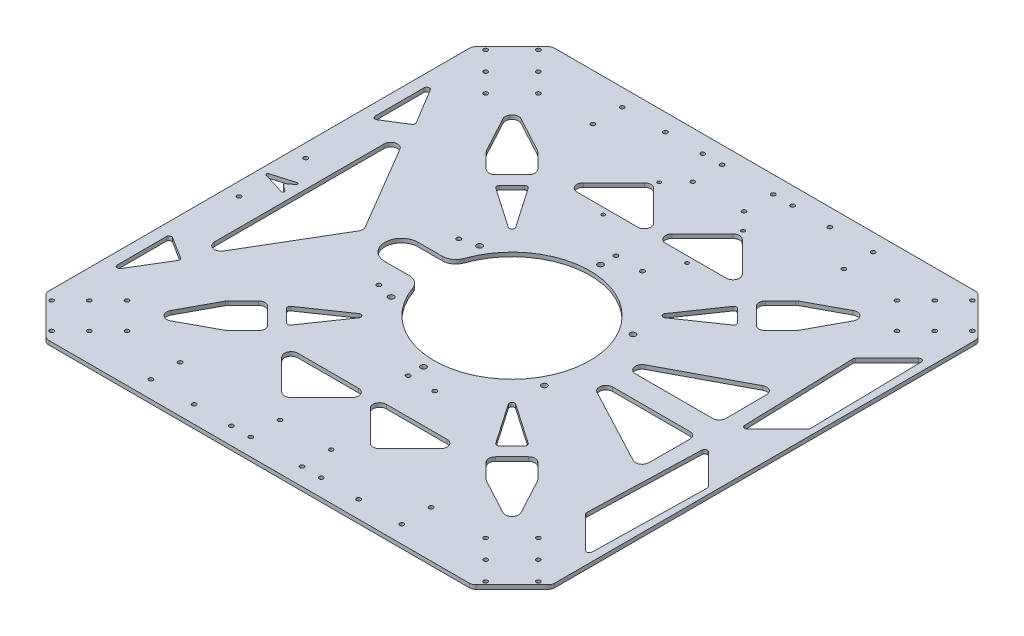
SolidWorks part; units mm, degrees
material "Hexcel AS4C (3000 丝)"
ref_plane "前视基准面" through (0, 0, 0) normal (0, 0, 1) x (1, 0, 0)
ref_plane "上视基准面" through (0, 0, 0) normal (0, 1, 0) x (1, 0, 0)
ref_plane "右视基准面" through (0, 0, 0) normal (1, 0, 0) x (0, 0, -1)
sketch "草图1" plane through (0, 0, 0) normal (0, 1, 0) x (1, 0, 0)
  line L0 (-190, 160) -> (-160, 190)
  line L1 (-160, 190) -> (160, 190)
  line L2 (-190, 160) -> (-190, -160)
  line L3 (-160, -190) -> (160, -190)
  line L4 (190, 160) -> (190, -160)
  line L5 (-190, 190) -> (190, -190) construction
  line L6 (-190, -190) -> (190, 190) construction
  line L7 (-190, -160) -> (-160, -190)
  line L8 (160, -190) -> (190, -160)
  line L9 (160, 190) -> (190, 160)
  circle A0 centre (0, 0) radius 58.5
  point P0 (0, 0)
  dimension "D3" = 117
  dimension "D1" = 380
  dimension "D2" = 380
extrude "凸台-拉伸1" add sketch "草图1" along normal blind 3
sketch "草图2" plane through (0, 3, 0) normal (0, 1, 0) x (1, 0, 0)
  line L1 (33.5, -23.5) -> (-33.5, -23.5) construction
  line L2 (33.5, -23.5) -> (33.5, 23.5) construction
  line L3 (33.5, 23.5) -> (-33.5, 23.5) construction
  line L4 (-33.5, -23.5) -> (-33.5, 23.5) construction
  line L5 (33.5, -23.5) -> (-33.5, 23.5) construction
  line L6 (33.5, 23.5) -> (-33.5, -23.5) construction
  circle A0 centre (-33.5, 23.5) radius 1.6
  circle A1 centre (33.5, 23.5) radius 1.6
  circle A2 centre (33.5, -23.5) radius 1.6
  circle A3 centre (-33.5, -23.5) radius 1.6
  point P0 (0, 0)
  dimension "D3" = 3.2
  dimension "D1" = 67
  dimension "D2" = 47
extrude "切除-拉伸1" [suppressed] cut sketch "草图2" against normal through all
sketch "草图3" plane through (0, 3, 0) normal (0, 1, 0) x (1, 0, 0)
  line L0 (0, 0) -> (-175, -175) construction
  line L1 (-190, -160) -> (-160, -190) construction
  line L2 (-162.9792, -182.7782) -> (-134.6949, -154.4939) construction
  circle A1 centre (-162.9792, -182.7782) radius 1.55
  circle A2 centre (-182.7782, -162.9792) radius 1.55
  circle A3 centre (-148.837, -168.636) radius 1.55
  circle A4 centre (-134.6949, -154.4939) radius 1.55
  circle A5 centre (-168.636, -148.837) radius 1.55
  circle A6 centre (-154.4939, -134.6949) radius 1.55
  circle A7 centre (-162.9792, 182.7782) radius 1.55
  circle A8 centre (-148.837, 168.636) radius 1.55
  circle A9 centre (-134.6949, 154.4939) radius 1.55
  circle A10 centre (-154.4939, 134.6949) radius 1.55
  circle A11 centre (-168.636, 148.837) radius 1.55
  circle A12 centre (-182.7782, 162.9792) radius 1.55
  circle A13 centre (182.7782, 162.9792) radius 1.55
  circle A14 centre (168.636, 148.837) radius 1.55
  circle A15 centre (154.4939, 134.6949) radius 1.55
  circle A16 centre (134.6949, 154.4939) radius 1.55
  circle A17 centre (148.837, 168.636) radius 1.55
  circle A18 centre (162.9792, 182.7782) radius 1.55
  circle A19 centre (162.9792, -182.7782) radius 1.55
  circle A20 centre (148.837, -168.636) radius 1.55
  circle A21 centre (134.6949, -154.4939) radius 1.55
  circle A22 centre (154.4939, -134.6949) radius 1.55
  circle A23 centre (168.636, -148.837) radius 1.55
  circle A24 centre (182.7782, -162.9792) radius 1.55
  point P56 (0, 0)
  dimension "D1" = 3.1
  dimension "D2" = 28
  dimension "D3" = 3
  dimension "D4" = 20
  dimension "D5" = 4
extrude "切除-拉伸2" cut sketch "草图3" against normal through all
sketch "草图5" plane through (0, 3, 4) normal (0, 1, 0) x (1, 0, 0)
  line L0 (56.75, 174.8369) -> (56.75, 11.178) construction
  line L2 (-89.25, 194) -> (-89.25, 166)
  line L9 (19.25, 181) -> (94.25, 181) construction
  line L10 (15, 194) -> (118.5, 194) construction
  line L11 (15, 194) -> (15, 156.5) construction
  line L12 (15, 156.5) -> (118.5, 156.5) construction
  line L13 (118.5, 194) -> (118.5, 156.5) construction
  line L14 (15, 194) -> (118.5, 156.5) construction
  line L15 (15, 156.5) -> (118.5, 194) construction
  line L16 (19.25, 181) -> (19.25, 159) construction
  line L17 (19.25, 159) -> (94.25, 159) construction
  line L18 (94.25, 159) -> (94.25, 181) construction
  line L19 (89.25, 194) -> (89.25, 166)
  line L20 (89.25, 166) -> (24.25, 166)
  line L21 (24.25, 166) -> (24.25, 194)
  line L22 (89.25, 194) -> (24.25, 194)
  line L42 (0, 0) -> (0, 194) construction
  line L43 (160, 194) -> (-160, 194) construction
  line L44 (-89.25, 166) -> (-24.25, 166)
  line L45 (-24.25, 166) -> (-24.25, 194)
  line L46 (-89.25, 194) -> (-24.25, 194)
  line L47 (0, 4) -> (-190, 4) construction
  line L48 (-190, 164) -> (-190, -156) construction
  line L49 (94.25, -151) -> (94.25, -173) construction
  line L50 (19.25, -151) -> (94.25, -151) construction
  line L51 (19.25, -173) -> (19.25, -151) construction
  line L52 (15, -148.5) -> (118.5, -186) construction
  line L53 (15, -186) -> (118.5, -148.5) construction
  line L54 (118.5, -186) -> (118.5, -148.5) construction
  line L55 (15, -148.5) -> (118.5, -148.5) construction
  line L56 (15, -186) -> (15, -148.5) construction
  line L57 (15, -186) -> (118.5, -186) construction
  line L58 (19.25, -173) -> (94.25, -173) construction
  line L59 (-89.25, -186) -> (-24.25, -186)
  line L60 (-24.25, -158) -> (-24.25, -186)
  line L61 (-89.25, -158) -> (-24.25, -158)
  line L62 (89.25, -186) -> (24.25, -186)
  line L63 (24.25, -158) -> (24.25, -186)
  line L64 (89.25, -158) -> (24.25, -158)
  line L65 (89.25, -186) -> (89.25, -158)
  line L66 (-89.25, -186) -> (-89.25, -158)
  circle A4 centre (19.25, 181) radius 1.55
  circle A5 centre (94.25, 181) radius 1.55
  circle A6 centre (19.25, 159) radius 1.55
  circle A7 centre (94.25, 159) radius 1.55
  circle A8 centre (-94.25, 181) radius 1.55
  circle A9 centre (-94.25, 159) radius 1.55
  circle A10 centre (-19.25, 181) radius 1.55
  circle A11 centre (-19.25, 159) radius 1.55
  circle A12 centre (-19.25, -151) radius 1.55
  circle A13 centre (-19.25, -173) radius 1.55
  circle A14 centre (-94.25, -151) radius 1.55
  circle A15 centre (-94.25, -173) radius 1.55
  circle A16 centre (94.25, -151) radius 1.55
  circle A17 centre (19.25, -151) radius 1.55
  circle A18 centre (94.25, -173) radius 1.55
  circle A19 centre (19.25, -173) radius 1.55
  point P5 (66.75, 175.25)
  point P67 (66.75, -167.25)
  point P84 (0, 0)
  dimension "D3" = 8.5
  dimension "D4" = 13
  dimension "D5" = 3.1
  dimension "D7" = 22
  dimension "D8" = 15
  dimension "D1" = 103.5
  dimension "D2" = 37.5
  dimension "D6" = 75
  dimension "D9" = 5
  dimension "D10" = 15
  dimension "D11" = 65
extrude "切除-拉伸3" [suppressed] cut sketch "草图5" against normal through all
sketch "草图6" plane through (0, 3, 0) normal (0, 1, 0) x (1, 0, 0)
  line L0 (0, 0) -> (190, 0) construction
  line L1 (190, -160) -> (190, 160) construction
  line L2 (187, 0) -> (162, -7.5) construction
  line L3 (162, -7.5) -> (172, 0) construction
  line L4 (187, 0) -> (162, 7.5) construction
  line L5 (162, 7.5) -> (172, 0) construction
  line L6 (0, 0) -> (0, 270.8739) construction
  line L7 (-187, 0) -> (-162, -7.5)
  line L8 (-162, -7.5) -> (-172, 0)
  line L9 (-162, 7.5) -> (-172, 0)
  line L10 (-187, 0) -> (-162, 7.5)
  dimension "D1" = 3
  dimension "D2" = 15
  dimension "D3" = 15
  dimension "D4" = 25
extrude "切除-拉伸4" cut sketch "草图6" against normal through all
fillet "圆角1" radius 1 4 edges at (-162, 1.5, -7.5) (-162, 1.5, 7.5) (-187, 1.5, 0) (-172, 1.5, 0)
sketch "草图7" plane through (0, 3, 0) normal (0, 1, 0) x (1, 0, 0)
  line L0 (160, 190) -> (-160, 190) construction
  line L1 (19.25, 177) -> (94.25, 177) construction
  line L2 (15, 190) -> (118.5, 190) construction
  line L3 (15, 190) -> (15, 152.5) construction
  line L4 (15, 152.5) -> (118.5, 152.5) construction
  line L5 (118.5, 190) -> (118.5, 152.5) construction
  line L6 (15, 190) -> (118.5, 152.5) construction
  line L7 (15, 152.5) -> (118.5, 190) construction
  line L8 (19.25, 177) -> (19.25, 155) construction
  line L9 (19.25, 155) -> (94.25, 155) construction
  line L10 (94.25, 155) -> (94.25, 177) construction
  line L11 (0, 0) -> (0, 200) construction
  line L12 (0, 0) -> (-190, 0) construction
  line L13 (-190, 160) -> (-190, -160) construction
  line L14 (94.25, -155) -> (94.25, -177) construction
  line L15 (19.25, -155) -> (94.25, -155) construction
  line L16 (19.25, -177) -> (19.25, -155) construction
  line L17 (15, -152.5) -> (118.5, -190) construction
  line L18 (15, -190) -> (118.5, -152.5) construction
  line L19 (118.5, -190) -> (118.5, -152.5) construction
  line L20 (15, -152.5) -> (118.5, -152.5) construction
  line L21 (15, -190) -> (15, -152.5) construction
  line L22 (15, -190) -> (118.5, -190) construction
  line L23 (19.25, -177) -> (94.25, -177) construction
  circle A0 centre (19.25, 177) radius 1.55
  circle A1 centre (94.25, 177) radius 1.55
  circle A2 centre (19.25, 155) radius 1.55
  circle A3 centre (94.25, 155) radius 1.55
  circle A4 centre (33.75, 177) radius 1.55
  circle A5 centre (61.75, 177) radius 1.55
  circle A6 centre (-94.25, 177) radius 1.55
  circle A7 centre (-94.25, 155) radius 1.55
  circle A8 centre (-61.75, 177) radius 1.55
  circle A9 centre (-33.75, 177) radius 1.55
  circle A10 centre (-19.25, 177) radius 1.55
  circle A11 centre (-19.25, 155) radius 1.55
  circle A12 centre (61.75, -177) radius 1.55
  circle A13 centre (33.75, -177) radius 1.55
  circle A14 centre (94.25, -155) radius 1.55
  circle A15 centre (19.25, -155) radius 1.55
  circle A16 centre (94.25, -177) radius 1.55
  circle A17 centre (19.25, -177) radius 1.55
  circle A18 centre (-19.25, -155) radius 1.55
  circle A19 centre (-19.25, -177) radius 1.55
  circle A20 centre (-33.75, -177) radius 1.55
  circle A21 centre (-61.75, -177) radius 1.55
  circle A22 centre (-94.25, -155) radius 1.55
  circle A23 centre (-94.25, -177) radius 1.55
  point P3 (66.75, 171.25)
  point P53 (66.75, -171.25)
  dimension "D4" = 3.1
  dimension "D1" = 103.5
  dimension "D2" = 37.5
  dimension "D3" = 8.5
  dimension "D5" = 13
  dimension "D6" = 75
  dimension "D7" = 22
  dimension "D8" = 14.5
  dimension "D9" = 28
  dimension "D10" = 15
extrude "切除-拉伸5" cut sketch "草图7" against normal through all
sketch "草图8" plane through (0, 3, 0) normal (0, 1, 0) x (1, 0, 0)
  line L0 (0, 0) -> (-190, 0) construction
  line L1 (-190, 160) -> (-190, -160) construction
  circle A0 centre (-180, 25) radius 1.55
  circle A1 centre (-180, -25) radius 1.55
  dimension "D1" = 3.1
  dimension "D2" = 50
  dimension "D3" = 10
extrude "切除-拉伸6" cut sketch "草图8" against normal through all
sketch "草图9" plane through (0, 3, 0) normal (0, 1, 0) x (1, 0, 0)
  line L0 (0, 0) -> (0, -66.5) construction
  line L1 (0, 0) -> (-190, 0) construction
  line L2 (-190, 160) -> (-190, -160) construction
  line L3 (-83, -12.5) -> (-57.1489, -12.5)
  line L4 (-83, 12.5) -> (-57.1489, 12.5)
  circle A0 centre (0, 0) radius 66.5 construction
  circle A1 centre (0, -66.5) radius 2.1
  circle A2 centre (-57.5907, -33.25) radius 2.1
  circle A3 centre (-57.5907, 33.25) radius 2.1
  circle A4 centre (0, 66.5) radius 2.1
  circle A5 centre (57.5907, 33.25) radius 2.1
  circle A6 centre (57.5907, -33.25) radius 2.1
  arc A7 (-83, 12.5) -> (-83, -12.5) centre (-83, 0) ccw
  circle A8 centre (0, 0) radius 58.5 construction
  arc A9 (-57.1489, 12.5) -> (-57.1489, -12.5) centre (0, 0) ccw
  point P17 (0, 0)
  dimension "D1" = 133
  dimension "D2" = 4.2
  dimension "D4" = 25
  dimension "D5" = 83
  dimension "D3" = 6
extrude "切除-拉伸7" cut sketch "草图9" against normal through all
fillet "圆角2" radius 10 2 edges at (-57.1489, 1.5, -12.5) (-57.1489, 1.5, 12.5)
sketch "草图10" plane through (0, 3, 0) normal (0, 1, 0) x (1, 0, 0)
  line L0 (0, 0) -> (0, 190) construction
  line L1 (160, 190) -> (-160, 190) construction
  line L3 (31.5, 100) -> (-31.5, 100) construction
  line L4 (31.5, 100) -> (31.5, 142) construction
  line L5 (31.5, 142) -> (-31.5, 142) construction
  line L6 (-31.5, 100) -> (-31.5, 142) construction
  line L7 (31.5, 100) -> (-31.5, 142) construction
  line L8 (31.5, 142) -> (-31.5, 100) construction
  circle A0 centre (-31.5, 142) radius 1.3
  circle A1 centre (31.5, 142) radius 1.3
  circle A2 centre (31.5, 100) radius 1.3
  circle A3 centre (-31.5, 100) radius 1.3
  point P5 (0, 121)
  dimension "D4" = 2.6
  dimension "D1" = 63
  dimension "D2" = 42
  dimension "D3" = 100
extrude "切除-拉伸8" cut sketch "草图10" against normal through all
sketch "草图11" plane through (0, 0, 0) normal (0, -1, 0) x (1, 0, 0)
  line L0 (0, 0) -> (-95.5, 0) construction
  arc A0 (-83, 12.5) -> (-83, -12.5) centre (-83, 0) ccw construction
  circle A1 centre (-70, -30) radius 1.6
  circle A2 centre (-70, 30) radius 1.6
  dimension "D1" = 60
  dimension "D2" = 3.2
  dimension "D3" = 70
extrude "切除-拉伸9" cut sketch "草图11" against normal through all
sketch "草图12" plane through (0, 0, 0) normal (0, -1, 0) x (1, 0, 0)
  line L0 (0, 0) -> (0, 190) construction
  line L1 (-160, 190) -> (160, 190) construction
  line L2 (20, 78) -> (0, 78) construction
  line L3 (0, 0) -> (-95.5, 0) construction
  circle A0 centre (20, 78) radius 1.6
  circle A1 centre (0, 78) radius 1.6
  arc A2 (-55.2542, -19.2153) -> (-55.2542, 19.2153) centre (0, 0) ccw construction
  arc A3 (-83, 12.5) -> (-83, -12.5) centre (-83, 0) ccw construction
  circle A4 centre (0, -78) radius 1.6
  circle A5 centre (20, -78) radius 1.6
  dimension "D1" = 3.2
  dimension "D2" = 20
  dimension "D3" = 78
extrude "切除-拉伸10" cut sketch "草图12" against normal through all
fillet "圆角3" radius 5 8 edges at (160, 1.5, -190) (190, 1.5, 160) (160, 1.5, 190) (-160, 1.5, 190) (-190, 1.5, 160) (-190, 1.5, -160) (-160, 1.5, -190) (190, 1.5, -160)
sketch "草图13" plane through (0, 3, 0) normal (0, 1, 0) x (1, 0, 0)
  line L0 (-98.0571, 117.1344) -> (-124.7458, 131.5195)
  line L2 (0, 0) -> (0, 233.6288) construction
  line L3 (0, 0) -> (221.2321, 0) construction
  line L16 (-131.5195, -124.7458) -> (-117.1344, -98.0571)
  line L17 (-116.2686, -96.8939) -> (-104.9705, -85.5958)
  line L18 (-97.8994, -85.5958) -> (-85.5958, -97.8994)
  line L19 (-85.5958, -104.9705) -> (-96.8939, -116.2686)
  line L20 (-98.0571, -117.1344) -> (-124.7458, -131.5195)
  line L21 (117.1344, 98.0571) -> (131.5195, 124.7458)
  line L22 (104.9705, 85.5958) -> (116.2686, 96.8939)
  line L23 (85.5958, 97.8994) -> (97.8994, 85.5958)
  line L24 (96.8939, 116.2686) -> (85.5958, 104.9705)
  line L25 (124.7458, 131.5195) -> (98.0571, 117.1344)
  line L29 (-85.5958, 104.9705) -> (-96.8939, 116.2686)
  line L30 (-97.8994, 85.5958) -> (-85.5958, 97.8994)
  line L31 (-116.2686, 96.8939) -> (-104.9705, 85.5958)
  line L32 (-131.5195, 124.7458) -> (-117.1344, 98.0571)
  line L36 (98.0571, -117.1344) -> (124.7458, -131.5195)
  line L37 (85.5958, -104.9705) -> (96.8939, -116.2686)
  line L38 (97.8994, -85.5958) -> (85.5958, -97.8994)
  line L39 (116.2686, -96.8939) -> (104.9705, -85.5958)
  line L40 (131.5195, -124.7458) -> (117.1344, -98.0571)
  arc A8 (-96.8939, -116.2686) -> (-98.0571, -117.1344) centre (-100.4294, -112.733) cw
  arc A9 (-85.5958, -97.8994) -> (-85.5958, -104.9705) centre (-89.1314, -101.435) cw
  arc A10 (-104.9705, -85.5958) -> (-97.8994, -85.5958) centre (-101.435, -89.1314) cw
  arc A11 (-117.1344, -98.0571) -> (-116.2686, -96.8939) centre (-112.733, -100.4294) cw
  arc A12 (-131.5195, -124.7458) -> (-124.7458, -131.5195) centre (-127.1181, -127.1181) ccw
  arc A13 (124.7458, 131.5195) -> (131.5195, 124.7458) centre (127.1181, 127.1181) cw
  arc A14 (98.0571, 117.1344) -> (96.8939, 116.2686) centre (100.4294, 112.733) ccw
  arc A15 (85.5958, 104.9705) -> (85.5958, 97.8994) centre (89.1314, 101.435) ccw
  arc A16 (97.8994, 85.5958) -> (104.9705, 85.5958) centre (101.435, 89.1314) ccw
  arc A17 (116.2686, 96.8939) -> (117.1344, 98.0571) centre (112.733, 100.4294) ccw
  arc A21 (-131.5195, 124.7458) -> (-124.7458, 131.5195) centre (-127.1181, 127.1181) cw
  arc A22 (-117.1344, 98.0571) -> (-116.2686, 96.8939) centre (-112.733, 100.4294) ccw
  arc A23 (-104.9705, 85.5958) -> (-97.8994, 85.5958) centre (-101.435, 89.1314) ccw
  arc A24 (-85.5958, 97.8994) -> (-85.5958, 104.9705) centre (-89.1314, 101.435) ccw
  arc A25 (-96.8939, 116.2686) -> (-98.0571, 117.1344) centre (-100.4294, 112.733) ccw
  arc A29 (131.5195, -124.7458) -> (124.7458, -131.5195) centre (127.1181, -127.1181) cw
  arc A30 (117.1344, -98.0571) -> (116.2686, -96.8939) centre (112.733, -100.4294) ccw
  arc A31 (104.9705, -85.5958) -> (97.8994, -85.5958) centre (101.435, -89.1314) ccw
  arc A32 (85.5958, -97.8994) -> (85.5958, -104.9705) centre (89.1314, -101.435) ccw
  arc A33 (96.8939, -116.2686) -> (98.0571, -117.1344) centre (100.4294, -112.733) ccw
  point P23 (-97.4121, -116.7867)
  point P30 (-116.7867, -97.4121)
  point P39 (-139.4391, -139.4391)
  point P64 (139.4391, 139.4391)
  point P67 (97.4121, 116.7867)
  point P68 (116.7867, 97.4121)
  point P79 (-139.4391, 139.4391)
  point P82 (-116.7867, 97.4121)
  point P83 (-97.4121, 116.7867)
  point P108 (139.4391, -139.4391)
  point P111 (116.7867, -97.4121)
  point P112 (97.4121, -116.7867)
  dimension "D1" = 5
extrude "切除-拉伸11" cut sketch "草图13" against normal through all
sketch "草图14" plane through (0, 0, 0) normal (0, -1, 0) x (1, 0, 0)
  line L0 (0, 0) -> (0, 207.8819) construction
  line L1 (59.5795, 113.3602) -> (36.78, 136.1597)
  line L2 (29.709, 136.1597) -> (6.9095, 113.3602)
  line L3 (10.445, 104.8247) -> (56.044, 104.8247)
  line L4 (0, 0) -> (244.1182, 0) construction
  line L5 (139.6526, 48.6248) -> (81.8263, 17.9529)
  line L6 (84.1692, 8.5358) -> (142.1513, 8.5358)
  line L7 (147.1512, 13.5612) -> (146.9954, 44.2331)
  line L8 (147.1512, -13.5612) -> (146.9954, -44.2331)
  line L9 (84.1692, -8.5358) -> (142.1513, -8.5358)
  line L10 (139.6526, -48.6248) -> (81.8263, -17.9529)
  line L14 (-159.7409, 63.746) -> (-159.7409, -63.746)
  line L15 (-150.4355, 66.2882) -> (-112.7947, 2.5423)
  line L16 (-112.7947, -2.5423) -> (-150.4355, -66.2882)
  line L17 (0, 0) -> (-241.6808, 0) construction
  line L18 (183.7106, -128.4099) -> (156.0282, -100.7275)
  line L19 (156.0282, -100.7275) -> (158.8315, -11.3728)
  line L20 (158.8315, -11.3728) -> (185.4627, -38.004)
  line L21 (185.4627, -38.004) -> (183.7106, -128.4099)
  line L22 (158.8315, 11.3728) -> (185.4627, 38.004)
  line L23 (156.0282, 100.7275) -> (158.8315, 11.3728)
  line L24 (183.7106, 128.4099) -> (156.0282, 100.7275)
  line L25 (185.4627, 38.004) -> (183.7106, 128.4099)
  line L26 (29.709, -136.1597) -> (6.9095, -113.3602)
  line L27 (59.5795, -113.3602) -> (36.78, -136.1597)
  line L28 (10.445, -104.8247) -> (56.044, -104.8247)
  line L29 (-59.5795, -113.3602) -> (-36.78, -136.1597)
  line L30 (-10.445, -104.8247) -> (-56.044, -104.8247)
  line L31 (-29.709, -136.1597) -> (-6.9095, -113.3602)
  line L32 (-29.709, 136.1597) -> (-6.9095, 113.3602)
  line L33 (-59.5795, 113.3602) -> (-36.78, 136.1597)
  line L34 (-10.445, 104.8247) -> (-56.044, 104.8247)
  arc A1 (-159.7409, -63.746) -> (-150.4355, -66.2882) centre (-154.7409, -63.746) ccw
  arc A2 (-159.7409, 63.746) -> (-150.4355, 66.2882) centre (-154.7409, 63.746) cw
  arc A3 (-112.7947, 2.5423) -> (-112.7947, -2.5423) centre (-117.1001, 0) cw
  arc A7 (59.5795, 113.3602) -> (56.044, 104.8247) centre (56.044, 109.8247) cw
  arc A8 (36.78, 136.1597) -> (29.709, 136.1597) centre (33.2445, 132.6242) ccw
  arc A9 (6.9095, 113.3602) -> (10.445, 104.8247) centre (10.445, 109.8247) ccw
  arc A10 (146.9954, -44.2331) -> (139.6526, -48.6248) centre (141.9955, -44.2077) cw
  arc A11 (84.1692, -8.5358) -> (81.8263, -17.9529) centre (84.1692, -13.5358) ccw
  arc A12 (142.1513, -8.5358) -> (147.1512, -13.5612) centre (142.1513, -13.5358) cw
  arc A13 (81.8263, 17.9529) -> (84.1692, 8.5358) centre (84.1692, 13.5358) ccw
  arc A14 (139.6526, 48.6248) -> (146.9954, 44.2331) centre (141.9955, 44.2077) cw
  arc A15 (142.1513, 8.5358) -> (147.1512, 13.5612) centre (142.1513, 13.5358) ccw
  arc A438 (36.78, -136.1597) -> (29.709, -136.1597) centre (33.2445, -132.6242) cw
  arc A439 (59.5795, -113.3602) -> (56.044, -104.8247) centre (56.044, -109.8247) ccw
  arc A440 (6.9095, -113.3602) -> (10.445, -104.8247) centre (10.445, -109.8247) cw
  arc A441 (-36.78, -136.1597) -> (-29.709, -136.1597) centre (-33.2445, -132.6242) ccw
  arc A442 (-59.5795, -113.3602) -> (-56.044, -104.8247) centre (-56.044, -109.8247) cw
  arc A443 (-6.9095, -113.3602) -> (-10.445, -104.8247) centre (-10.445, -109.8247) ccw
  arc A444 (-36.78, 136.1597) -> (-29.709, 136.1597) centre (-33.2445, 132.6242) cw
  arc A445 (-59.5795, 113.3602) -> (-56.044, 104.8247) centre (-56.044, 109.8247) ccw
  arc A446 (-6.9095, 113.3602) -> (-10.445, 104.8247) centre (-10.445, 109.8247) cw
  point P23 (-159.7409, -82.0473)
  point P28 (-159.7409, 82.0473)
  point P31 (-111.2935, 0)
  point P34 (-68.1151, 104.8247)
  point P40 (1.6261, 104.8247)
  point P43 (68.1151, 104.8247)
  point P46 (33.2445, 139.6953)
  point P49 (-1.6261, 104.8247)
  point P52 (146.9534, -52.4972)
  point P55 (64.0721, -8.5358)
  point P58 (147.1767, -8.5358)
  point P61 (64.0721, 8.5358)
  point P64 (146.9534, 52.4972)
  point P67 (147.1767, 8.5358)
  dimension "D1" = 5
extrude "切除-拉伸12" cut sketch "草图14" against normal through all
sketch "草图15" plane through (0, 0, 0) normal (0, -1, 0) x (1, 0, 0)
  line L0 (0, 0) -> (-91.7476, -91.7476) construction
  line L1 (-97.8994, -85.5958) -> (-85.5958, -97.8994) construction
  line L5 (-78.2655, -91.0876) -> (-91.0876, -78.2655)
  line L6 (-91.0876, -78.2655) -> (-50.0163, -50.0163)
  line L7 (-78.2655, -91.0876) -> (-50.0163, -50.0163)
  line L8 (-91.0876, 78.2655) -> (-78.2655, 91.0876)
  line L9 (-78.2655, 91.0876) -> (-50.0163, 50.0163)
  line L10 (-91.0876, 78.2655) -> (-50.0163, 50.0163)
  line L11 (78.2655, 91.0876) -> (91.0876, 78.2655)
  line L12 (91.0876, 78.2655) -> (50.0163, 50.0163)
  line L13 (78.2655, 91.0876) -> (50.0163, 50.0163)
  line L14 (91.0876, -78.2655) -> (78.2655, -91.0876)
  line L15 (78.2655, -91.0876) -> (50.0163, -50.0163)
  line L16 (91.0876, -78.2655) -> (50.0163, -50.0163)
  point P9 (-84.6766, -84.6766)
  point P21 (0, 0)
  dimension "D2" = 10
  dimension "D1" = 4
extrude "切除-拉伸13" cut sketch "草图15" against normal through all
fillet "圆角4" radius 2 20 edges at (183.7106, 1.5, -128.4099) (156.0282, 1.5, -100.7275) (158.8315, 1.5, -11.3728) (185.4627, 1.5, -38.004) (183.7106, 1.5, 128.4099) (185.4627, 1.5, 38.004) (158.8315, 1.5, 11.3728) (156.0282, 1.5, 100.7275) (-50.0163, 1.5, -50.0163) (-91.0876, 1.5, 78.2655) (-78.2655, 1.5, 91.0876) (-50.0163, 1.5, 50.0163) (78.2655, 1.5, 91.0876) (91.0876, 1.5, 78.2655) (50.0163, 1.5, 50.0163) (91.0876, 1.5, -78.2655) (78.2655, 1.5, -91.0876) (50.0163, 1.5, -50.0163) (-78.2655, 1.5, -91.0876) (-91.0876, 1.5, -78.2655)
sketch "草图16" plane through (0, 0, 0) normal (0, -1, 0) x (1, 0, 0)
  line L0 (-181.2514, -122.3897) -> (-181.2514, -74.8045)
  line L1 (-181.2514, -74.8045) -> (-160.4549, -87.8464)
  line L2 (-160.4549, -87.8464) -> (-181.2514, -122.3897)
  line L3 (0, 0) -> (-159.7409, 0) construction
  line L4 (-159.7409, 63.746) -> (-159.7409, -63.746) construction
  line L5 (-181.2514, 74.8045) -> (-160.4549, 87.8464)
  line L6 (-181.2514, 122.3897) -> (-181.2514, 74.8045)
  line L7 (-160.4549, 87.8464) -> (-181.2514, 122.3897)
extrude "切除-拉伸14" cut sketch "草图16" against normal through all
fillet "圆角5" radius 2 6 edges at (-160.4549, 1.5, 87.8464) (-181.2514, 1.5, 74.8045) (-181.2514, 1.5, 122.3897) (-181.2514, 1.5, -74.8045) (-160.4549, 1.5, -87.8464) (-181.2514, 1.5, -122.3897)
